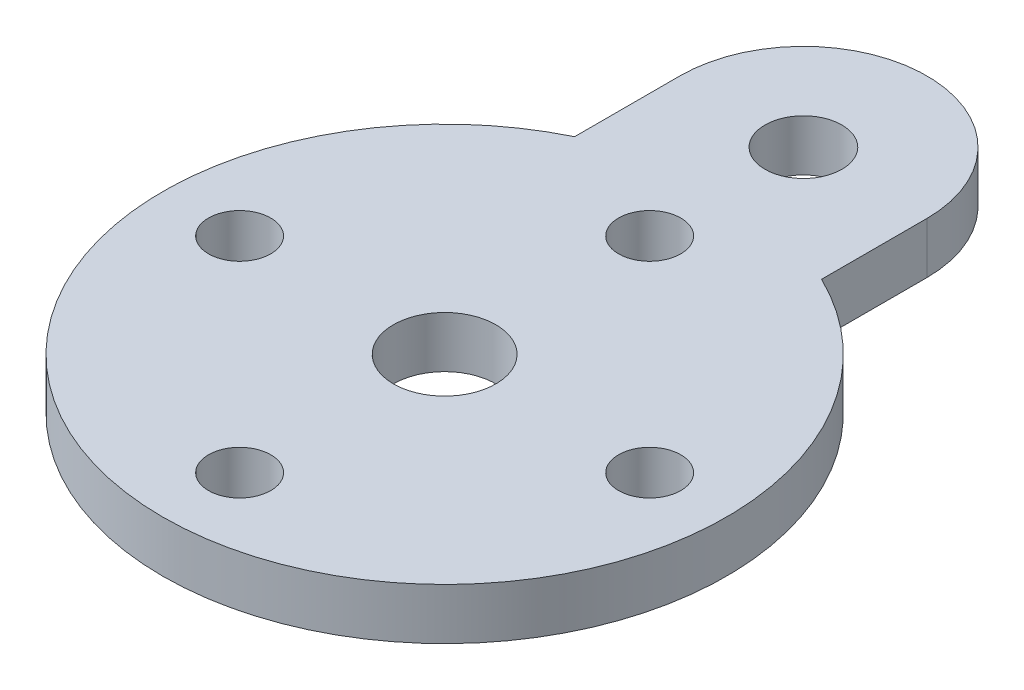
SolidWorks part; units mm, degrees
ref_plane "Спереди" through (0, 0, 0) normal (0, 0, 1) x (1, 0, 0)
ref_plane "Сверху" through (0, 0, 0) normal (0, 1, 0) x (1, 0, 0)
ref_plane "Справа" through (0, 0, 0) normal (1, 0, 0) x (0, 0, -1)
sketch "Sketch1" plane through (0, 0, 0) normal (0, 1, 0) x (1, 0, 0)
  line L0 (-4.8181, 14) -> (-4.8181, 9.8887)
  line L1 (4.8181, 14) -> (4.8181, 9.8887)
  arc A0 (-4.8181, 9.8887) -> (4.8181, 9.8887) centre (0, 0) ccw
  circle A1 centre (0, 8) radius 1.2134
  circle A2 centre (8, 0) radius 1.2134
  circle A3 centre (0, -8) radius 1.2134
  circle A4 centre (-8, 0) radius 1.2134
  circle A5 centre (0, 0) radius 2
  arc A6 (-4.8181, 14) -> (4.8181, 14) centre (0, 14) cw
  circle A7 centre (0, 14) radius 1.5
  point P14 (0, 0)
  dimension "D1" = 8
  dimension "D3" = 11
  dimension "D4" = 14
  dimension "D2" = 4
extrude "Boss-Extrude1" add sketch "Sketch1" along normal blind 2
